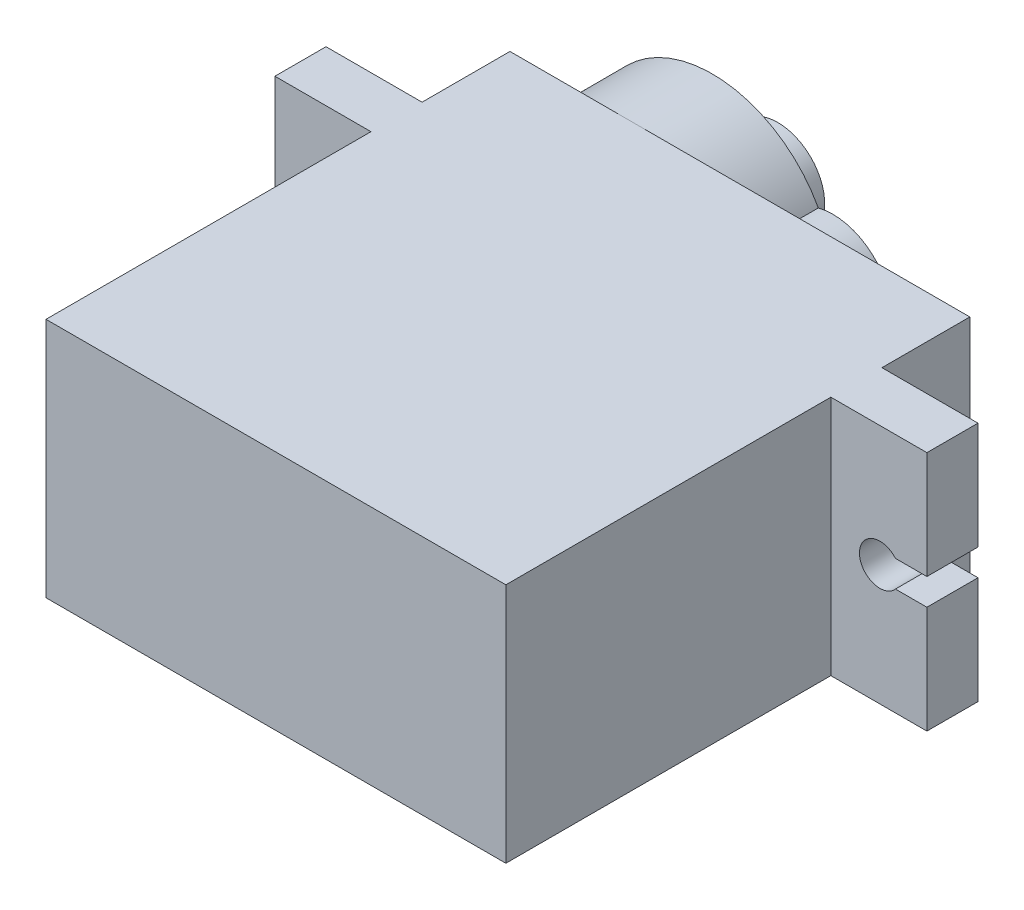
SolidWorks part; units mm, degrees
material "ABS"
ref_plane "Front Plane" through (0, 0, 0) normal (0, 0, 1) x (1, 0, 0)
ref_plane "Top Plane" through (0, 0, 0) normal (0, 1, 0) x (1, 0, 0)
ref_plane "Right Plane" through (0, 0, 0) normal (1, 0, 0) x (0, 0, -1)
sketch "Sketch1" plane through (0, 0, 0) normal (0, 1, 0) x (1, 0, 0)
  line L1 (-11.25, -11.7821) -> (11.25, -11.7821)
  line L2 (-11.25, -11.7821) -> (-11.25, 10.9179)
  line L3 (-11.25, 10.9179) -> (11.25, 10.9179)
  line L4 (11.25, -11.7821) -> (11.25, 10.9179)
  dimension "D1" = 22.7
  dimension "D2" = 22.5
  dimension "D3" = 11.25
extrude "Boss-Extrude1" add sketch "Sketch1" along normal blind 11.8
sketch "Sketch2" plane through (0, 11.8, 0) normal (0, 1, 0) x (1, 0, 0)
  line L0 (11.25, -11.7821) -> (11.25, 10.9179) construction
  line L1 (11.25, 6.6179) -> (15.95, 6.6179)
  line L2 (11.25, 6.6179) -> (11.25, 4.1179)
  line L3 (11.25, 4.1179) -> (15.95, 4.1179)
  line L4 (15.95, 6.6179) -> (15.95, 4.1179)
  line L5 (-11.25, -11.7821) -> (11.25, -11.7821) construction
  dimension "D1" = 15.9
  dimension "D2" = 2.5
  dimension "D3" = 4.7
extrude "Boss-Extrude2" add sketch "Sketch2" against normal blind 11.8
sketch "Sketch3" plane through (0, 11.8, 0) normal (0, 1, 0) x (1, 0, 0)
  line L0 (-11.25, 10.9179) -> (-11.25, -11.7821) construction
  line L1 (-11.25, 6.6179) -> (-15.95, 6.6179)
  line L2 (-11.25, 6.6179) -> (-11.25, 4.1179)
  line L3 (-11.25, 4.1179) -> (-15.95, 4.1179)
  line L4 (-15.95, 6.6179) -> (-15.95, 4.1179)
  line L7 (-11.25, -11.7821) -> (11.25, -11.7821) construction
  dimension "D1" = 2.5
  dimension "D2" = 4.7
  dimension "D3" = 15.9
extrude "Boss-Extrude3" add sketch "Sketch3" against normal blind 11.8
sketch "Sketch4" plane through (0, 0, -10.9179) normal (0, 0, -1) x (-1, 0, 0)
  line L1 (11.25, 0) -> (11.25, 11.8) construction
  line L2 (-11.25, 11.8) -> (11.25, 11.8) construction
  circle A0 centre (5.35, 5.9) radius 5.9
  dimension "D1" = 5.9
  dimension "D2" = 5.9
extrude "Boss-Extrude4" add sketch "Sketch4" along normal blind 4
sketch "Sketch5" plane through (0, 0, -14.9179) normal (0, 0, -1) x (-1, 0, 0)
  circle A0 centre (-0.55, 5.9) radius 2.9
  circle A1 centre (5.35, 5.9) radius 5.9 construction
extrude "Boss-Extrude5" add sketch "Sketch5" against normal blind 4
sketch "Sketch6" plane through (0, 0, -6.6179) normal (0, 0, -1) x (-1, 0, 0)
  line L0 (-15.95, 0) -> (-15.95, 11.8) construction
  line L1 (-15.95, 6.55) -> (-13.65, 6.55)
  line L2 (-15.95, 6.55) -> (-15.95, 5.25)
  line L3 (-15.95, 5.25) -> (-13.65, 5.25)
  line L4 (-13.65, 6.55) -> (-13.65, 5.25)
  line L5 (-15.95, 11.8) -> (-11.25, 11.8) construction
  line L6 (14.2827, 6.819) -> (16.5827, 6.819)
  line L7 (14.2827, 6.819) -> (14.2827, 5.519)
  line L8 (14.2827, 5.519) -> (16.5827, 5.519)
  line L9 (16.5827, 6.819) -> (16.5827, 5.519)
  circle A0 centre (-13.65, 5.9) radius 1
  dimension "D1" = 1.3
  dimension "D2" = 2.3
  dimension "D3" = 5.25
extrude "Cut-Extrude5" cut sketch "Sketch6" against normal through all contours L2 L1 L4 L3 | A0
sketch "Sketch8" plane through (0, 0, -6.6179) normal (0, 0, -1) x (-1, 0, 0)
  line L0 (15.95, 0) -> (15.95, 11.8) construction
  line L1 (15.95, 6.55) -> (13.65, 6.55)
  line L2 (15.95, 6.55) -> (15.95, 5.25)
  line L3 (15.95, 5.25) -> (13.65, 5.25)
  line L4 (13.65, 6.55) -> (13.65, 5.25)
  line L6 (11.25, 11.8) -> (15.95, 11.8) construction
  circle A0 centre (13.65, 5.9) radius 1
  dimension "D1" = 1.3
  dimension "D2" = 2.3
  dimension "D3" = 5.25
extrude "Cut-Extrude7" cut sketch "Sketch8" against normal through all contours L1 A0 L3 L4
sketch "Sketch9" plane through (0, 0, -14.9179) normal (0, 0, -1) x (-1, 0, 0)
  line L0 (11.25, 0) -> (11.25, 11.8) construction
  circle A1 centre (5.35, 5.8429) radius 2.3
  circle A2 centre (5.35, 5.8429) radius 0.85
  dimension "D1" = 5.9
extrude "Boss-Extrude7" add sketch "Sketch9" along normal blind 3.2
